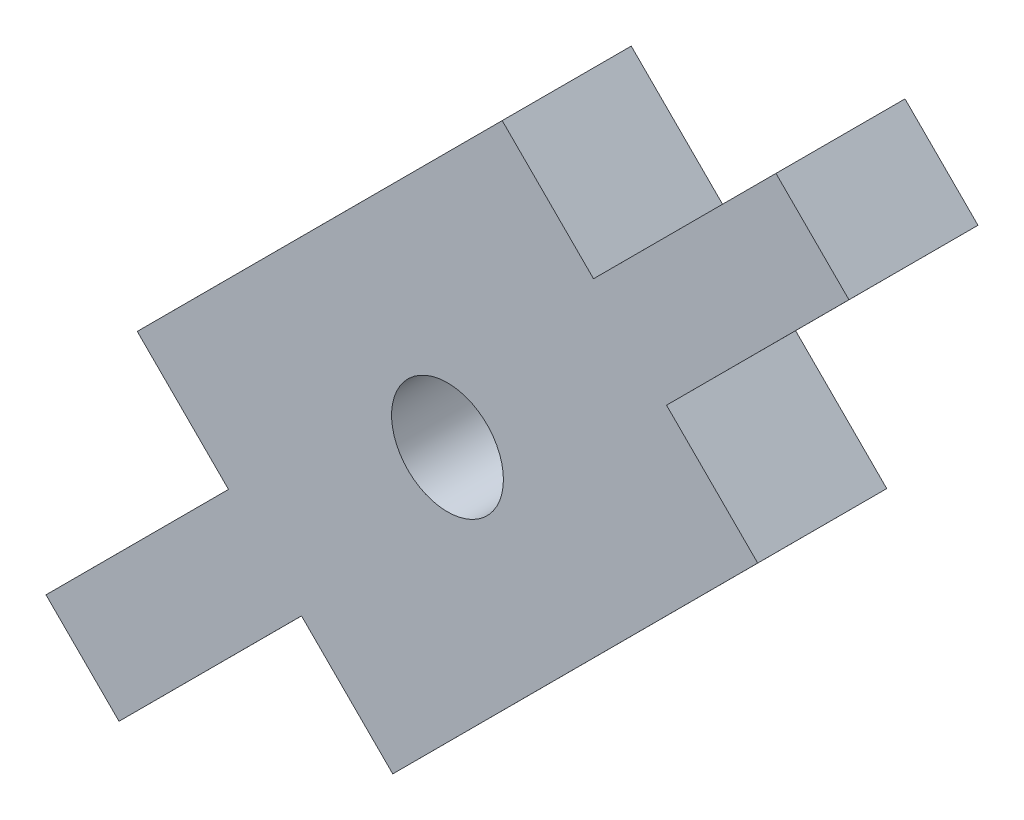
SolidWorks part; units mm, degrees
ref_plane "前视基准面" through (0, 0, 0) normal (0, 0, 1) x (1, 0, 0)
ref_plane "上视基准面" through (0, 0, 0) normal (0, 1, 0) x (1, 0, 0)
ref_plane "右视基准面" through (0, 0, 0) normal (1, 0, 0) x (0, 0, -1)
ref_plane "基准面4" through (0, 0, -0.3629) normal (0, 0, 1) x (1, 0, 0)
sketch "草图1" plane through (0, 0, -0.3629) normal (0, 0, 1) x (1, 0, 0)
  line L0 (6.932, 27.6854) -> (4.8084, 29.8083)
  line L1 (4.8084, 29.8083) -> (-3.6758, 21.3217)
  line L2 (-3.6758, 21.3217) -> (-1.5545, 19.201)
  line L3 (-1.5545, 19.201) -> (-5.7975, 14.9569)
  line L4 (-5.7975, 14.9569) -> (-4.0998, 13.2597)
  line L5 (-4.0998, 13.2597) -> (0.1425, 17.5032)
  line L6 (0.1425, 17.5032) -> (2.2643, 15.3821)
  line L7 (2.2643, 15.3821) -> (10.7491, 23.8693)
  line L8 (10.7491, 23.8693) -> (8.6291, 25.9887)
  line L9 (8.6291, 25.9887) -> (12.8704, 30.2312)
  line L10 (12.8704, 30.2312) -> (11.1732, 31.9279)
  line L11 (11.1732, 31.9279) -> (6.932, 27.6854)
  circle A0 centre (3.5366, 22.594) radius 1.3
extrude "凸台-拉伸1" add sketch "草图1" against normal blind 3
